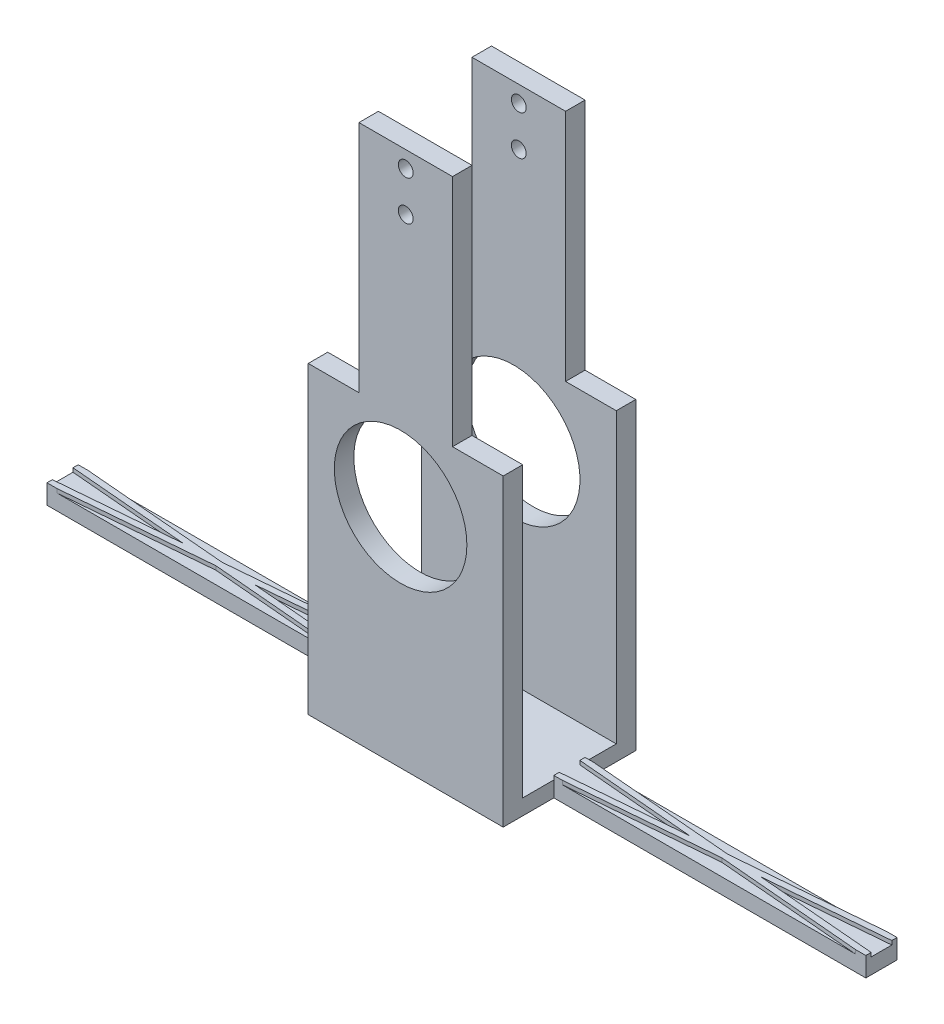
SolidWorks part; units mm, degrees
ref_plane "Front Plane" through (0, 0, 0) normal (0, 0, 1) x (1, 0, 0)
ref_plane "Top Plane" through (0, 0, 0) normal (0, 1, 0) x (1, 0, 0)
ref_plane "Right Plane" through (0, 0, 0) normal (1, 0, 0) x (0, 0, -1)
sketch "Sketch1" plane through (0, 0, 0) normal (0, 1, 0) x (1, 0, 0)
  line L1 (-37.9471, -101.2298) -> (-12.9471, -101.2298)
  line L2 (-37.9471, -101.2298) -> (-37.9471, -118.2298)
  line L3 (-37.9471, -118.2298) -> (-12.9471, -118.2298)
  line L4 (-12.9471, -101.2298) -> (-12.9471, -118.2298)
  line L5 (-37.9471, -111.7298) -> (-77.9471, -111.7298)
  line L6 (-37.9471, -111.7298) -> (-37.9471, -107.7298)
  line L7 (-37.9471, -107.7298) -> (-77.9471, -107.7298)
  line L8 (-77.9471, -111.7298) -> (-77.9471, -107.7298)
  line L9 (27.0529, -111.7298) -> (27.0529, -107.7298)
  line L10 (-12.9471, -107.7298) -> (27.0529, -107.7298)
  line L11 (-12.9471, -111.7298) -> (27.0529, -111.7298)
  dimension "D1" = 17
  dimension "D2" = 40
  dimension "20" = 25
  dimension "D3" = 4
  dimension "D4" = 6.5
  dimension "D5" = 6.5
extrude "Boss-Extrude1" add sketch "Sketch1" along normal blind 2 contours L8 L5 L2 L7 | L4 L1 L2 L3 | L4 L11 L9 L10
sketch "Sketch2" plane through (0, 2, 0) normal (0, 1, 0) x (1, 0, 0)
  line L0 (-39.0519, -111.7298) -> (-77.9471, -108.3974)
  line L1 (-37.9471, -111.7298) -> (-77.9471, -111.7298) construction
  line L2 (-77.9471, -111.7298) -> (-77.9471, -107.7298) construction
  line L3 (-39.0519, -111.7298) -> (-37.9471, -111.7298)
  line L4 (-37.9471, -111.7298) -> (-37.9471, -111.0447)
  line L5 (-37.9471, -111.0447) -> (-76.6382, -107.7298)
  line L6 (-37.9471, -107.7298) -> (-77.9471, -107.7298) construction
  line L7 (-76.6382, -107.7298) -> (-77.9471, -107.7298)
  line L8 (-77.9471, -107.7298) -> (-77.9471, -108.3974)
  line L9 (-77.9471, -111.7298) -> (-76.6382, -111.7298)
  line L10 (-76.6382, -111.7298) -> (-37.9471, -108.3974)
  line L11 (-37.9471, -108.3974) -> (-37.9471, -107.7298)
  line L12 (-37.9471, -107.7298) -> (-39.0519, -107.7298)
  line L13 (-39.0519, -107.7298) -> (-77.9471, -111.0447)
  line L14 (-77.9471, -111.0447) -> (-77.9471, -111.7298)
  line L15 (-76.6382, -111.7298) -> (-77.9471, -111.7298)
  line L20 (27.0529, -111.0447) -> (27.0529, -111.7298)
  line L21 (27.0529, -111.7298) -> (25.744, -111.7298)
  line L22 (-12.9471, -108.3974) -> (-12.9471, -107.7298)
  line L23 (-12.9471, -107.7298) -> (-11.8423, -107.7298)
  line L24 (-11.8423, -107.7298) -> (27.0529, -111.0447)
  line L25 (25.744, -111.7298) -> (-12.9471, -108.3974)
  line L26 (-12.9471, -111.0447) -> (25.744, -107.7298)
  line L27 (-11.8423, -111.7298) -> (27.0529, -108.3974)
  line L28 (-11.8423, -111.7298) -> (-12.9471, -111.7298)
  line L29 (-12.9471, -111.7298) -> (-12.9471, -111.0447)
  line M1 (-77.9471, -107.7298) -> (-77.9471, -111.7298)
  line M2 (-77.9471, -111.7298) -> (-37.9471, -111.7298)
  line M8 (-37.9471, -107.7298) -> (-77.9471, -107.7298)
  line M25 (-12.9471, -111.7298) -> (27.0529, -111.7298)
  line M26 (27.0529, -111.7298) -> (27.0529, -107.7298)
  line M27 (27.0529, -107.7298) -> (-12.9471, -107.7298)
extrude "Boss-Extrude2" add sketch "Sketch2" along normal blind 0.5 contours L13 L5 L0 M8 M1 | L0 L13 L10 M1 M2 | L10 L0 L4 L5 M2 | L5 L13 L0 L10 | L13 L5 L10 L11 M8 | L29 L27 L25 L26 M25 | L25 L26 L24 L22 M27 | L25 L27 L24 L26 | L27 L25 L24 M25 M26 | L24 L27 L26 M26 M27
sketch "Sketch3" plane through (0, 2, 0) normal (0, 1, 0) x (1, 0, 0)
  line L0 (-12.9471, -101.2298) -> (-12.9471, -107.7298) construction
  line L1 (-37.9471, -118.2298) -> (-12.9471, -118.2298)
  line L2 (-37.9471, -118.2298) -> (-37.9471, -115.7298)
  line L3 (-37.9471, -115.7298) -> (-12.9471, -115.7298)
  line L4 (-12.9471, -118.2298) -> (-12.9471, -115.7298)
  line L5 (-37.9471, -101.2298) -> (-37.9471, -107.7298) construction
  line L6 (-12.9471, -101.2298) -> (-37.9471, -101.2298)
  line L7 (-12.9471, -101.2298) -> (-12.9471, -103.7298)
  line L8 (-12.9471, -103.7298) -> (-37.9471, -103.7298)
  line L9 (-37.9471, -101.2298) -> (-37.9471, -103.7298)
  dimension "D1" = 2.5
  dimension "D2" = 2.5
  dimension "D3" = 12
extrude "Boss-Extrude3" add sketch "Sketch3" along normal blind 37
sketch "Sketch4" plane through (0, 0, 118.2298) normal (0, 0, 1) x (1, 0, 0)
  line L0 (-37.9471, 39) -> (-12.9471, 39) construction
  circle A0 centre (-26.1022, 29) radius 8.5
  dimension "D1" = 17
  dimension "D3" = 27
  dimension "D2" = 10
extrude "Cut-Extrude1" cut sketch "Sketch4" against normal blind 37
sketch "Sketch6" plane through (0, 39, 0) normal (0, 1, 0) x (1, 0, 0)
  line L0 (-37.9471, -118.2298) -> (-12.9471, -118.2298) construction
  line L1 (-31.4471, -118.2298) -> (-19.4471, -118.2298)
  line L2 (-31.4471, -118.2298) -> (-31.4471, -115.7298)
  line L3 (-31.4471, -115.7298) -> (-19.4471, -115.7298)
  line L4 (-19.4471, -118.2298) -> (-19.4471, -115.7298)
  line L5 (-12.9471, -115.7298) -> (-37.9471, -115.7298) construction
  line L6 (-37.9471, -103.7298) -> (-12.9471, -103.7298) construction
  line L7 (-31.4471, -103.7298) -> (-19.4471, -103.7298)
  line L8 (-31.4471, -103.7298) -> (-31.4471, -101.2298)
  line L9 (-31.4471, -101.2298) -> (-19.4471, -101.2298)
  line L10 (-19.4471, -103.7298) -> (-19.4471, -101.2298)
  line L11 (-12.9471, -101.2298) -> (-37.9471, -101.2298) construction
  line L12 (-37.9471, -115.7298) -> (-37.9471, -118.2298) construction
  line L13 (-12.9471, -118.2298) -> (-12.9471, -115.7298) construction
  line L14 (-37.9471, -101.2298) -> (-37.9471, -103.7298) construction
  line L15 (-12.9471, -103.7298) -> (-12.9471, -101.2298) construction
  point P18 (-37.9471, -116.9798)
  dimension "D1" = 12
  dimension "D2" = 6.5
  dimension "D3" = 6.5
  dimension "D4" = 12
  dimension "D5" = 6.5
  dimension "D6" = 6.5
extrude "Boss-Extrude4" add sketch "Sketch6" along normal blind 30
sketch "Sketch8" plane through (0, 0, 118.2298) normal (0, 0, 1) x (1, 0, 0)
  line L0 (-31.4471, 69) -> (-31.4471, 39) construction
  line L1 (-19.4471, 69) -> (-19.4471, 39) construction
  circle A0 centre (-25.4471, 66.8727) radius 0.95
  circle A1 centre (-25.4471, 61.7745) radius 0.95
  dimension "D1" = 1.9
  dimension "D2" = 1.9
  dimension "D3" = 6
  dimension "D4" = 6
  dimension "D5" = 6
extrude "Cut-Extrude2" cut sketch "Sketch8" against normal blind 30
